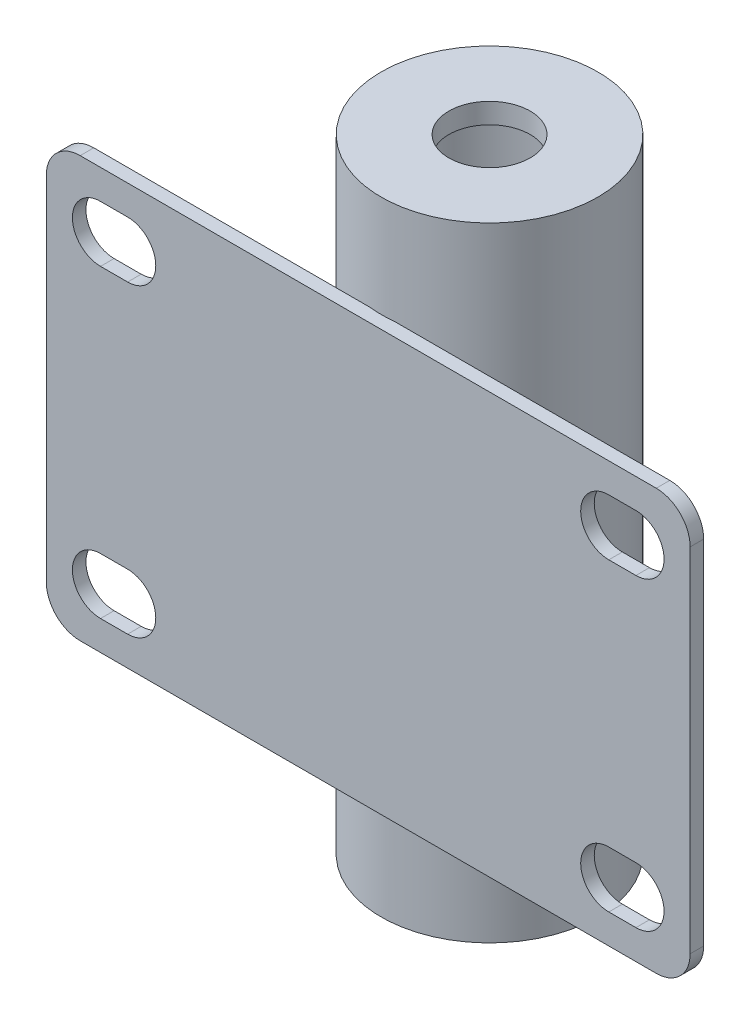
SolidWorks part; units mm, degrees
ref_plane "前视基准面" through (0, 0, 0) normal (0, 0, 1) x (1, 0, 0)
ref_plane "上视基准面" through (0, 0, 0) normal (0, 1, 0) x (1, 0, 0)
ref_plane "右视基准面" through (0, 0, 0) normal (1, 0, 0) x (0, 0, -1)
sketch "草图1" plane through (0, 0, 0) normal (0, 0, 1) x (1, 0, 0)
  line L0 (-39.5, 22.5) -> (-35.5, 22.5) construction
  line L1 (47.5, -31) -> (-47.5, -31)
  line L2 (47.5, -31) -> (47.5, 31)
  line L3 (47.5, 31) -> (-47.5, 31)
  line L4 (-47.5, -31) -> (-47.5, 31)
  line L5 (47.5, -31) -> (-47.5, 31) construction
  line L6 (47.5, 31) -> (-47.5, -31) construction
  line L7 (-39.5, 26.65) -> (-35.5, 26.65)
  line L8 (-39.5, 18.35) -> (-35.5, 18.35)
  line L9 (0, 0) -> (0, 24.1135) construction
  line L10 (0, 0) -> (-37.3325, 0) construction
  line L11 (39.5, 22.5) -> (35.5, 22.5) construction
  line L12 (39.5, 26.65) -> (35.5, 26.65)
  line L13 (39.5, 18.35) -> (35.5, 18.35)
  line L14 (-39.5, -22.5) -> (-35.5, -22.5) construction
  line L15 (-39.5, -26.65) -> (-35.5, -26.65)
  line L16 (-39.5, -18.35) -> (-35.5, -18.35)
  line L17 (39.5, -22.5) -> (35.5, -22.5) construction
  line L18 (39.5, -26.65) -> (35.5, -26.65)
  line L19 (39.5, -18.35) -> (35.5, -18.35)
  arc A0 (-39.5, 26.65) -> (-39.5, 18.35) centre (-39.5, 22.5) ccw
  arc A1 (-35.5, 18.35) -> (-35.5, 26.65) centre (-35.5, 22.5) ccw
  arc A2 (39.5, 26.65) -> (39.5, 18.35) centre (39.5, 22.5) cw
  arc A3 (35.5, 18.35) -> (35.5, 26.65) centre (35.5, 22.5) cw
  arc A4 (-39.5, -26.65) -> (-39.5, -18.35) centre (-39.5, -22.5) cw
  arc A5 (-35.5, -18.35) -> (-35.5, -26.65) centre (-35.5, -22.5) cw
  arc A6 (39.5, -26.65) -> (39.5, -18.35) centre (39.5, -22.5) ccw
  arc A7 (35.5, -18.35) -> (35.5, -26.65) centre (35.5, -22.5) ccw
  point P0 (0, 0)
  point P8 (-37.5, 22.5)
  point P18 (37.5, 22.5)
  point P25 (-37.5, -22.5)
  point P32 (37.5, -22.5)
  dimension "D3" = 4.15
  dimension "D1" = 95
  dimension "D2" = 62
  dimension "D4" = 4
  dimension "D5" = 75
  dimension "D6" = 45
extrude "凸台-拉伸1" add sketch "草图1" along normal blind 2
sketch "草图2" plane through (0, 31, 0) normal (0, 1, 0) x (1, 0, 0)
  line L1 (47.5, 0) -> (-47.5, 0) construction
  circle A0 centre (0, 15.9) radius 16
  dimension "D1" = 32
  dimension "D2" = 15.9
extrude "凸台-拉伸2" add sketch "草图2" along normal blind 15 and the other way blind 77
fillet "圆角1" radius 5 4 edges at (47.5, -31, 1) (-47.5, -31, 1) (-47.5, 31, 1) (47.5, 31, 1)
sketch "草图3" plane through (0, 46, 0) normal (0, 1, 0) x (1, 0, 0)
  circle A0 centre (0, 15.9) radius 13
  circle A1 centre (0, 15.9) radius 16
  circle A2 centre (0, 15.9) radius 16 construction
  dimension "D1" = 0
  dimension "D2" = 3
extrude "切除-拉伸3" cut sketch "草图3" against normal through all from offset 3 offset against normal yes
sketch "草图5" plane through (0, 43, 0) normal (0, -1, 0) x (-1, 0, 0)
  circle A0 centre (0, 15.9) radius 6
  dimension "D1" = 12
extrude "切除-拉伸4" cut sketch "草图5" against normal through all
